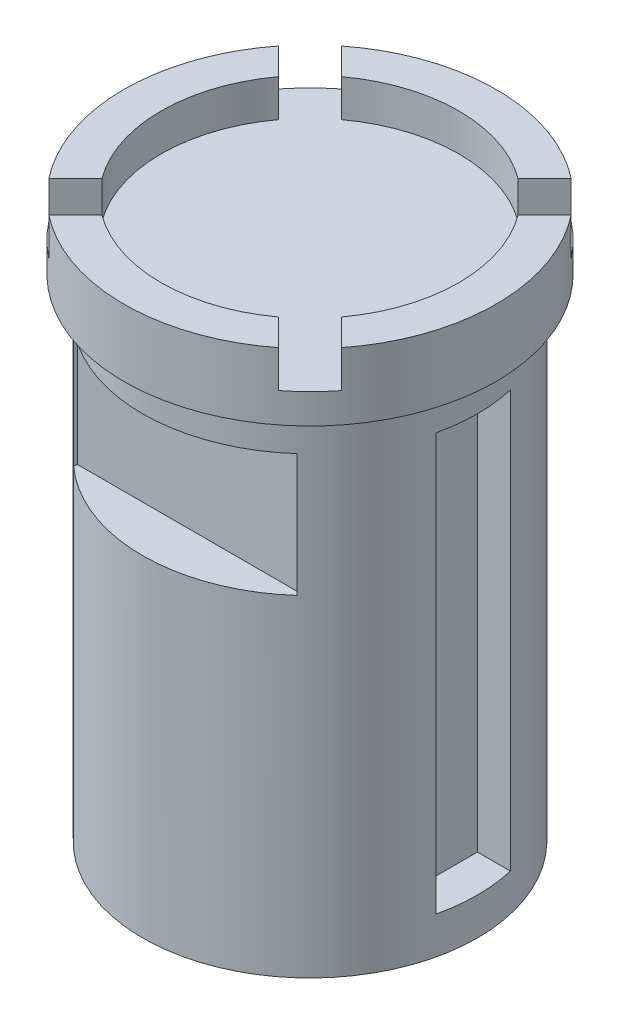
SolidWorks part; units mm, degrees
other "Satellite Body"
ref_plane "Front Plane" through (0, 0, 0) normal (0, 0, 1) x (1, 0, 0)
ref_plane "Top Plane" through (0, 0, 0) normal (0, 1, 0) x (1, 0, 0)
ref_plane "Right Plane" through (0, 0, 0) normal (1, 0, 0) x (0, 0, -1)
sketch "Body Block Sketch" plane through (0, 0, 0) normal (0, 0, 1) x (1, 0, 0)
  line L1 (0, 0) -> (400, 0)
  line L2 (0, 0) -> (0, -1400)
  line L3 (0, -1400) -> (450, -1400)
  line L6 (450, 0) -> (450, -80) construction
  line L9 (500, 0) -> (500, 100)
  line L13 (500, 100) -> (400, 100)
  line L14 (400, 0) -> (400, 100)
  line L15 (400, 0) -> (450, 0) construction
  line L16 (450, 0) -> (400, 0) construction
  line L17 (450, -80) -> (450, -1400)
  line L18 (450, -80) -> (500, -80)
  line L19 (500, 0) -> (500, -80)
  line L21 (400, 0) -> (500, 0) construction
  dimension "D1" = 1400
  dimension "D2" = 500
  dimension "D3" = 50
  dimension "D4" = 100
  dimension "D5" = 100
  dimension "D6" = 80
revolve "Body Block Revolve" add sketch "Body Block Sketch" angle 360 about L2
ref_plane "Surface Feature Start Plane" through (0, -180, 0) normal (0, -1, 0) x (-1, 0, 0)
sketch "Solar Divot Sketch" plane through (0, -180, 0) normal (0, -1, 0) x (-1, 0, 0)
  line L0 (0, 0) -> (-450, 0) construction
  line L1 (-450, 100) -> (-350, 100)
  line L2 (-450, 100) -> (-450, -100)
  line L3 (-450, -100) -> (-350, -100)
  line L4 (-350, 100) -> (-350, -100)
  line L5 (0, -926.423) -> (0, 49073.577) construction
  line L6 (350, 100) -> (350, -100)
  line L7 (450, -100) -> (350, -100)
  line L8 (450, 100) -> (450, -100)
  line L9 (450, 100) -> (350, 100)
  circle A0 centre (0, 0) radius 450 construction
  dimension "D1" = 200
  dimension "D2" = 100
extrude "Solar Divot Cut" cut sketch "Solar Divot Sketch" along normal offset from surface (1120 mm away) 100 up to face at (-450, -1400, 0)
sketch "Misc Bay Sketch" plane through (0, -180, 0) normal (0, -1, 0) x (-1, 0, 0)
  line L0 (0, 0) -> (0, 450) construction
  line L1 (-300, 450) -> (300, 450)
  line L2 (-300, 450) -> (-300, 325.4102)
  line L3 (-300, 325.4102) -> (300, 325.4102)
  line L4 (300, 450) -> (300, 325.4102)
  line L5 (-3000, 0) -> (3000, 0) construction
  line L6 (300, -450) -> (300, -325.4102)
  line L7 (-300, -325.4102) -> (300, -325.4102)
  line L8 (-300, -450) -> (300, -450)
  line L9 (-300, -450) -> (-300, -325.4102)
  circle A0 centre (0, 0) radius 450 construction
  circle A2 centre (0, 0) radius 450 construction
  point P14 (0, 0)
  point P18 (300, 335.4102)
  dimension "D1" = 600
  dimension "D2" = 10
extrude "Misc Bay Cut" cut sketch "Misc Bay Sketch" along normal blind 330
sketch "Launch Adaptor Bay Sketch" plane through (0, -1400, 0) normal (0, -1, 0) x (1, 0, 0)
  circle A2 centre (0, 0) radius 370
  circle A3 centre (0, 0) radius 370
  dimension "D1" = 80
extrude "Launch Adaptor Bay Cut" cut sketch "Launch Adaptor Bay Sketch" against normal blind 40
sketch "Gripper Gap Sketch" plane through (0, 0, 0) normal (0, 1, 0) x (1, 0, 0)
  line L0 (0, 0) -> (0, 500) construction
  line L1 (311.127, 395.9798) -> (395.9798, 311.127)
  line L2 (311.127, 395.9798) -> (-42.4264, 42.4264)
  line L3 (-42.4264, 42.4264) -> (42.4264, -42.4264)
  line L4 (395.9798, 311.127) -> (42.4264, -42.4264)
  line L5 (0, 0) -> (353.5534, 353.5534) construction
  circle A0 centre (0, 0) radius 500 construction
  dimension "D1" = 120
  dimension "D2" = 500
  dimension "D3" = 45
extrude "Gripper Gap Cut" cut sketch "Gripper Gap Sketch" along normal up to surface (100 mm away) up to face at (-400, 100, 0)
pattern_circular "Gripper Gap Cut Propagation" count 4 over 360 about axis through (0, 0, 0) along (0, 1, 0) of "Gripper Gap Cut"
ref_plane "Gripper Lip Midplane" through (0, 50, 0) normal (0, 1, 0) x (1, 0, 0)
sketch "Gripper Gap Midpoint Sketch" plane through (0, 50, 0) normal (0, 1, 0) x (1, 0, 0)
  line L0 (353.5534, 353.5534) -> (282.8427, 282.8427) construction
  line L1 (282.8427, 282.8427) -> (0, 0) construction
  line L2 (0, 0) -> (353.5534, 353.5534) construction
  circle A0 centre (0, 0) radius 400 construction
  circle A1 centre (0, 0) radius 500 construction
  circle A2 centre (0, 0) radius 500 construction
  arc A3 (237.2162, 322.069) -> (-237.2162, 322.069) centre (0, 0) ccw construction
  point P11 (318.1981, 318.1981)
  point P14 (318.1981, 318.1981)
  point P18 (318.1981, -318.1981)
  point P19 (-318.1981, -318.1981)
  point P20 (-318.1981, 318.1981)
  point P21 (0, 0)
  dimension "D1" = 4
ref_point "Gripper Gap Midpoint Point"
